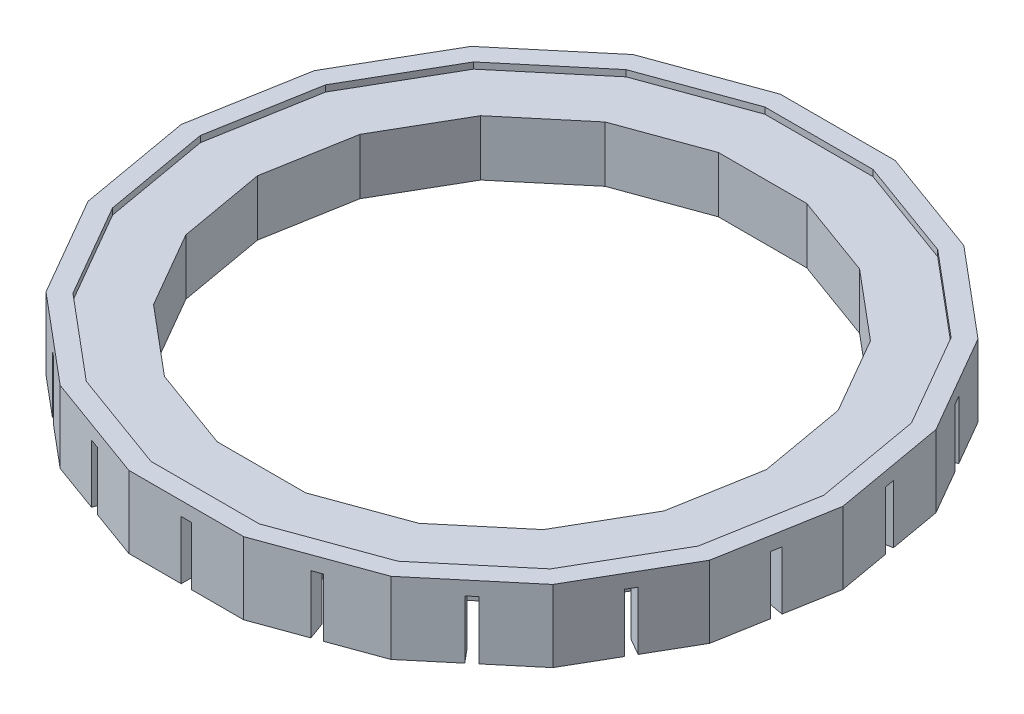
SolidWorks part; units mm, degrees
ref_plane "Front Plane" through (0, 0, 0) normal (0, 0, 1) x (1, 0, 0)
ref_plane "Top Plane" through (0, 0, 0) normal (0, 1, 0) x (1, 0, 0)
ref_plane "Right Plane" through (0, 0, 0) normal (1, 0, 0) x (0, 0, -1)
sketch "Sketch2" plane through (0, 0, 0) normal (0, 1, 0) x (1, 0, 0)
  line L1 (52.8022, 0) -> (49.6178, 18.0594)
  line L2 (49.6178, 18.0594) -> (40.4488, 33.9406)
  line L3 (40.4488, 33.9406) -> (26.4011, 45.728)
  line L4 (26.4011, 45.728) -> (9.169, 52)
  line L5 (9.169, 52) -> (-9.169, 52)
  line L6 (-9.169, 52) -> (-26.4011, 45.728)
  line L7 (-26.4011, 45.728) -> (-40.4488, 33.9406)
  line L8 (-40.4488, 33.9406) -> (-49.6178, 18.0594)
  line L9 (-49.6178, 18.0594) -> (-52.8022, 0)
  line L10 (-52.8022, 0) -> (-49.6178, -18.0594)
  line L11 (-49.6178, -18.0594) -> (-40.4488, -33.9406)
  line L12 (-40.4488, -33.9406) -> (-26.4011, -45.728)
  line L13 (-26.4011, -45.728) -> (-9.169, -52)
  line L14 (-9.169, -52) -> (9.169, -52)
  line L15 (9.169, -52) -> (26.4011, -45.728)
  line L16 (26.4011, -45.728) -> (40.4488, -33.9406)
  line L17 (40.4488, -33.9406) -> (49.6178, -18.0594)
  line L18 (49.6178, -18.0594) -> (52.8022, 0)
  circle A0 centre (0, 0) radius 52 construction
  dimension "D1" = 104
extrude "Boss-Extrude1" add sketch "Sketch2" along normal blind 11.5
sketch "Sketch3" plane through (0, 0, 0) normal (0, -1, 0) x (1, 0, 0)
  line L1 (40.6171, 0) -> (38.1676, 13.8919)
  line L2 (38.1676, 13.8919) -> (31.1145, 26.1081)
  line L3 (31.1145, 26.1081) -> (20.3085, 35.1754)
  line L4 (20.3085, 35.1754) -> (7.0531, 40)
  line L5 (7.0531, 40) -> (-7.0531, 40)
  line L6 (-7.0531, 40) -> (-20.3085, 35.1754)
  line L7 (-20.3085, 35.1754) -> (-31.1145, 26.1081)
  line L8 (-31.1145, 26.1081) -> (-38.1676, 13.8919)
  line L9 (-38.1676, 13.8919) -> (-40.6171, 0)
  line L10 (-40.6171, 0) -> (-38.1676, -13.8919)
  line L11 (-38.1676, -13.8919) -> (-31.1145, -26.1081)
  line L12 (-31.1145, -26.1081) -> (-20.3085, -35.1754)
  line L13 (-20.3085, -35.1754) -> (-7.0531, -40)
  line L14 (-7.0531, -40) -> (7.0531, -40)
  line L15 (7.0531, -40) -> (20.3085, -35.1754)
  line L16 (20.3085, -35.1754) -> (31.1145, -26.1081)
  line L17 (31.1145, -26.1081) -> (38.1676, -13.8919)
  line L18 (38.1676, -13.8919) -> (40.6171, 0)
  circle A0 centre (0, 0) radius 40 construction
  dimension "D1" = 80
extrude "Cut-Extrude1" cut sketch "Sketch3" against normal up to surface (11.5 mm away) up to face at (0, 11.5, 0)
sketch "Sketch4" plane through (0, 0, 0) normal (0, -1, 0) x (1, 0, 0)
  line L0 (-0.8, 52) -> (-0.8, 49)
  line L1 (-9.169, 52) -> (9.169, 52) construction
  line L2 (-0.8, 49) -> (-3.5, 49)
  line L3 (-3.5, 49) -> (-3.5, 41.9953)
  line L4 (-3.5, 41.9953) -> (3.5, 41.9953)
  line L5 (3.5, 41.9953) -> (3.5, 49)
  line L6 (3.5, 49) -> (0.8, 49)
  line L7 (0.8, 49) -> (0.8, 52)
  line L8 (0, 52) -> (0, 40) construction
  line L9 (7.0531, 40) -> (-7.0531, 40) construction
  line L10 (17.0333, 49.1376) -> (16.0072, 46.3186)
  line L11 (16.0072, 46.3186) -> (13.4701, 47.242)
  line L12 (13.4701, 47.242) -> (11.0743, 40.6598)
  line L13 (17.6522, 38.2656) -> (20.0479, 44.8479)
  line L14 (20.0479, 44.8479) -> (17.5107, 45.7713)
  line L15 (17.5107, 45.7713) -> (18.5368, 48.5904)
  line L16 (17.785, 48.864) -> (13.6808, 37.5877) construction
  line L17 (11.0743, 40.6598) -> (17.6522, 38.2656)
  line L18 (32.8121, 40.3485) -> (30.8838, 38.0504)
  line L19 (30.8838, 38.0504) -> (28.8154, 39.7859)
  line L20 (28.8154, 39.7859) -> (24.3129, 34.42)
  line L21 (29.6752, 29.9205) -> (34.1777, 35.2864)
  line L22 (34.1777, 35.2864) -> (32.1094, 37.0219)
  line L23 (32.1094, 37.0219) -> (34.0378, 39.3201)
  line L24 (33.425, 39.8343) -> (25.7115, 30.6418) construction
  line L25 (24.3129, 34.42) -> (29.6752, 29.9205)
  line L26 (44.6333, 26.6928) -> (42.0352, 25.1928)
  line L27 (42.0352, 25.1928) -> (40.6852, 27.5311)
  line L28 (40.6852, 27.5311) -> (34.619, 24.0287)
  line L29 (38.119, 17.9666) -> (44.1852, 21.4689)
  line L30 (44.1852, 21.4689) -> (42.8352, 23.8072)
  line L31 (42.8352, 23.8072) -> (45.4333, 25.3072)
  line L32 (45.0333, 26) -> (34.641, 20) construction
  line L33 (34.619, 24.0287) -> (38.119, 17.9666)
  line L34 (51.0711, 9.8176) -> (48.1167, 9.2966)
  line L35 (48.1167, 9.2966) -> (47.6478, 11.9556)
  line L36 (47.6478, 11.9556) -> (40.7495, 10.7392)
  line L37 (41.9651, 3.8456) -> (48.8633, 5.0619)
  line L38 (48.8633, 5.0619) -> (48.3945, 7.7209)
  line L39 (48.3945, 7.7209) -> (51.3489, 8.2419)
  line L40 (51.21, 9.0297) -> (39.3923, 6.9459) construction
  line L41 (40.7495, 10.7392) -> (41.9651, 3.8456)
  line L42 (51.3489, -8.2419) -> (48.3945, -7.7209)
  line L43 (48.3945, -7.7209) -> (48.8633, -5.0619)
  line L44 (48.8633, -5.0619) -> (41.9651, -3.8456)
  line L45 (40.7495, -10.7392) -> (47.6478, -11.9556)
  line L46 (47.6478, -11.9556) -> (48.1167, -9.2966)
  line L47 (48.1167, -9.2966) -> (51.0711, -9.8176)
  line L48 (51.21, -9.0297) -> (39.3923, -6.9459) construction
  line L49 (41.9651, -3.8456) -> (40.7495, -10.7392)
  line L50 (45.4333, -25.3072) -> (42.8352, -23.8072)
  line L51 (42.8352, -23.8072) -> (44.1852, -21.4689)
  line L52 (44.1852, -21.4689) -> (38.119, -17.9666)
  line L53 (34.619, -24.0287) -> (40.6852, -27.5311)
  line L54 (40.6852, -27.5311) -> (42.0352, -25.1928)
  line L55 (42.0352, -25.1928) -> (44.6333, -26.6928)
  line L56 (45.0333, -26) -> (34.641, -20) construction
  line L57 (38.119, -17.9666) -> (34.619, -24.0287)
  line L58 (34.0378, -39.3201) -> (32.1094, -37.0219)
  line L59 (32.1094, -37.0219) -> (34.1777, -35.2864)
  line L60 (34.1777, -35.2864) -> (29.6752, -29.9205)
  line L61 (24.3129, -34.42) -> (28.8154, -39.7859)
  line L62 (28.8154, -39.7859) -> (30.8838, -38.0504)
  line L63 (30.8838, -38.0504) -> (32.8121, -40.3485)
  line L64 (33.425, -39.8343) -> (25.7115, -30.6418) construction
  line L65 (29.6752, -29.9205) -> (24.3129, -34.42)
  line L66 (18.5368, -48.5904) -> (17.5107, -45.7713)
  line L67 (17.5107, -45.7713) -> (20.0479, -44.8479)
  line L68 (20.0479, -44.8479) -> (17.6522, -38.2656)
  line L69 (11.0743, -40.6598) -> (13.4701, -47.242)
  line L70 (13.4701, -47.242) -> (16.0072, -46.3186)
  line L71 (16.0072, -46.3186) -> (17.0333, -49.1376)
  line L72 (17.785, -48.864) -> (13.6808, -37.5877) construction
  line L73 (17.6522, -38.2656) -> (11.0743, -40.6598)
  line L74 (0.8, -52) -> (0.8, -49)
  line L75 (0.8, -49) -> (3.5, -49)
  line L76 (3.5, -49) -> (3.5, -41.9953)
  line L77 (-3.5, -41.9953) -> (-3.5, -49)
  line L78 (-3.5, -49) -> (-0.8, -49)
  line L79 (-0.8, -49) -> (-0.8, -52)
  line L80 (0, -52) -> (0, -40) construction
  line L81 (3.5, -41.9953) -> (-3.5, -41.9953)
  line L82 (-17.0333, -49.1376) -> (-16.0072, -46.3186)
  line L83 (-16.0072, -46.3186) -> (-13.4701, -47.242)
  line L84 (-13.4701, -47.242) -> (-11.0743, -40.6598)
  line L85 (-17.6522, -38.2656) -> (-20.0479, -44.8479)
  line L86 (-20.0479, -44.8479) -> (-17.5107, -45.7713)
  line L87 (-17.5107, -45.7713) -> (-18.5368, -48.5904)
  line L88 (-17.785, -48.864) -> (-13.6808, -37.5877) construction
  line L89 (-11.0743, -40.6598) -> (-17.6522, -38.2656)
  line L90 (-32.8121, -40.3485) -> (-30.8838, -38.0504)
  line L91 (-30.8838, -38.0504) -> (-28.8154, -39.7859)
  line L92 (-28.8154, -39.7859) -> (-24.3129, -34.42)
  line L93 (-29.6752, -29.9205) -> (-34.1777, -35.2864)
  line L94 (-34.1777, -35.2864) -> (-32.1094, -37.0219)
  line L95 (-32.1094, -37.0219) -> (-34.0378, -39.3201)
  line L96 (-33.425, -39.8343) -> (-25.7115, -30.6418) construction
  line L97 (-24.3129, -34.42) -> (-29.6752, -29.9205)
  line L98 (-44.6333, -26.6928) -> (-42.0352, -25.1928)
  line L99 (-42.0352, -25.1928) -> (-40.6852, -27.5311)
  line L100 (-40.6852, -27.5311) -> (-34.619, -24.0287)
  line L101 (-38.119, -17.9666) -> (-44.1852, -21.4689)
  line L102 (-44.1852, -21.4689) -> (-42.8352, -23.8072)
  line L103 (-42.8352, -23.8072) -> (-45.4333, -25.3072)
  line L104 (-45.0333, -26) -> (-34.641, -20) construction
  line L105 (-34.619, -24.0287) -> (-38.119, -17.9666)
  line L106 (-51.0711, -9.8176) -> (-48.1167, -9.2966)
  line L107 (-48.1167, -9.2966) -> (-47.6478, -11.9556)
  line L108 (-47.6478, -11.9556) -> (-40.7495, -10.7392)
  line L109 (-41.9651, -3.8456) -> (-48.8633, -5.0619)
  line L110 (-48.8633, -5.0619) -> (-48.3945, -7.7209)
  line L111 (-48.3945, -7.7209) -> (-51.3489, -8.2419)
  line L112 (-51.21, -9.0297) -> (-39.3923, -6.9459) construction
  line L113 (-40.7495, -10.7392) -> (-41.9651, -3.8456)
  line L114 (-51.3489, 8.2419) -> (-48.3945, 7.7209)
  line L115 (-48.3945, 7.7209) -> (-48.8633, 5.0619)
  line L116 (-48.8633, 5.0619) -> (-41.9651, 3.8456)
  line L117 (-40.7495, 10.7392) -> (-47.6478, 11.9556)
  line L118 (-47.6478, 11.9556) -> (-48.1167, 9.2966)
  line L119 (-48.1167, 9.2966) -> (-51.0711, 9.8176)
  line L120 (-51.21, 9.0297) -> (-39.3923, 6.9459) construction
  line L121 (-41.9651, 3.8456) -> (-40.7495, 10.7392)
  line L122 (-45.4333, 25.3072) -> (-42.8352, 23.8072)
  line L123 (-42.8352, 23.8072) -> (-44.1852, 21.4689)
  line L124 (-44.1852, 21.4689) -> (-38.119, 17.9666)
  line L125 (-34.619, 24.0287) -> (-40.6852, 27.5311)
  line L126 (-40.6852, 27.5311) -> (-42.0352, 25.1928)
  line L127 (-42.0352, 25.1928) -> (-44.6333, 26.6928)
  line L128 (-45.0333, 26) -> (-34.641, 20) construction
  line L129 (-38.119, 17.9666) -> (-34.619, 24.0287)
  line L130 (-34.0378, 39.3201) -> (-32.1094, 37.0219)
  line L131 (-32.1094, 37.0219) -> (-34.1777, 35.2864)
  line L132 (-34.1777, 35.2864) -> (-29.6752, 29.9205)
  line L133 (-24.3129, 34.42) -> (-28.8154, 39.7859)
  line L134 (-28.8154, 39.7859) -> (-30.8838, 38.0504)
  line L135 (-30.8838, 38.0504) -> (-32.8121, 40.3485)
  line L136 (-33.425, 39.8343) -> (-25.7115, 30.6418) construction
  line L137 (-29.6752, 29.9205) -> (-24.3129, 34.42)
  line L138 (-18.5368, 48.5904) -> (-17.5107, 45.7713)
  line L139 (-17.5107, 45.7713) -> (-20.0479, 44.8479)
  line L140 (-20.0479, 44.8479) -> (-17.6522, 38.2656)
  line L141 (-11.0743, 40.6598) -> (-13.4701, 47.242)
  line L142 (-13.4701, 47.242) -> (-16.0072, 46.3186)
  line L143 (-16.0072, 46.3186) -> (-17.0333, 49.1376)
  line L144 (-17.785, 48.864) -> (-13.6808, 37.5877) construction
  line L145 (-17.6522, 38.2656) -> (-11.0743, 40.6598)
  line L147 (-0.8, 52) -> (0.8, 52)
  line L148 (17.0333, 49.1376) -> (18.5368, 48.5904)
  line L149 (32.8121, 40.3485) -> (34.0378, 39.3201)
  line L150 (44.6333, 26.6928) -> (45.4333, 25.3072)
  line L151 (51.0711, 9.8176) -> (51.3489, 8.2419)
  line L152 (51.3489, -8.2419) -> (51.0711, -9.8176)
  line L153 (45.4333, -25.3072) -> (44.6333, -26.6928)
  line L154 (34.0378, -39.3201) -> (32.8121, -40.3485)
  line L155 (18.5368, -48.5904) -> (17.0333, -49.1376)
  line L156 (-0.8, -52) -> (0.8, -52)
  line L157 (-18.5368, -48.5904) -> (-17.0333, -49.1376)
  line L159 (-34.0378, -39.3201) -> (-32.8121, -40.3485)
  line L160 (-45.4333, -25.3072) -> (-44.6333, -26.6928)
  line L161 (-51.3489, -8.2419) -> (-51.0711, -9.8176)
  line L162 (-51.0711, 9.8176) -> (-51.3489, 8.2419)
  line L163 (-44.6333, 26.6928) -> (-45.4333, 25.3072)
  line L164 (-32.8121, 40.3485) -> (-34.0378, 39.3201)
  line L165 (-17.0333, 49.1376) -> (-18.5368, 48.5904)
  point P191 (0, 0)
  dimension "D1" = 0.0682
  dimension "D2" = 0.1325
  dimension "D3" = 1.348
  dimension "D4" = 1.4182
  dimension "D5" = 4.0163
  dimension "D7" = 18
extrude "Cut-Extrude3" cut sketch "Sketch4" against normal blind 9.3
sketch "Sketch5" plane through (0, 0, 0) normal (0, -1, 0) x (1, 0, 0)
  line L1 (49.75, 0) -> (46.7497, 17.0155)
  line L2 (46.7497, 17.0155) -> (38.1107, 31.9787)
  line L3 (38.1107, 31.9787) -> (24.875, 43.0848)
  line L4 (24.875, 43.0848) -> (8.639, 48.9942)
  line L5 (8.639, 48.9942) -> (-8.639, 48.9942)
  line L6 (-8.639, 48.9942) -> (-24.875, 43.0848)
  line L7 (-24.875, 43.0848) -> (-38.1107, 31.9787)
  line L8 (-38.1107, 31.9787) -> (-46.7497, 17.0155)
  line L9 (-46.7497, 17.0155) -> (-49.75, 0)
  line L10 (-49.75, 0) -> (-46.7497, -17.0155)
  line L11 (-46.7497, -17.0155) -> (-38.1107, -31.9787)
  line L12 (-38.1107, -31.9787) -> (-24.875, -43.0848)
  line L13 (-24.875, -43.0848) -> (-8.639, -48.9942)
  line L14 (-8.639, -48.9942) -> (8.639, -48.9942)
  line L15 (8.639, -48.9942) -> (24.875, -43.0848)
  line L16 (24.875, -43.0848) -> (38.1107, -31.9787)
  line L17 (38.1107, -31.9787) -> (46.7497, -17.0155)
  line L18 (46.7497, -17.0155) -> (49.75, 0)
  circle A0 centre (0, 0) radius 48.9942 construction
  dimension "D1" = 99.5
extrude "Cut-Extrude4" cut sketch "Sketch5" against normal blind 1.6
sketch "Sketch6" plane through (0, 11.5, 0) normal (0, 1, 0) x (1, 0, 0)
  line L1 (49.75, 0) -> (46.7497, 17.0155)
  line L2 (46.7497, 17.0155) -> (38.1107, 31.9787)
  line L3 (38.1107, 31.9787) -> (24.875, 43.0848)
  line L4 (24.875, 43.0848) -> (8.639, 48.9942)
  line L5 (8.639, 48.9942) -> (-8.639, 48.9942)
  line L6 (-8.639, 48.9942) -> (-24.875, 43.0848)
  line L7 (-24.875, 43.0848) -> (-38.1107, 31.9787)
  line L8 (-38.1107, 31.9787) -> (-46.7497, 17.0155)
  line L9 (-46.7497, 17.0155) -> (-49.75, 0)
  line L10 (-49.75, 0) -> (-46.7497, -17.0155)
  line L11 (-46.7497, -17.0155) -> (-38.1107, -31.9787)
  line L12 (-38.1107, -31.9787) -> (-24.875, -43.0848)
  line L13 (-24.875, -43.0848) -> (-8.639, -48.9942)
  line L14 (-8.639, -48.9942) -> (8.639, -48.9942)
  line L15 (8.639, -48.9942) -> (24.875, -43.0848)
  line L16 (24.875, -43.0848) -> (38.1107, -31.9787)
  line L17 (38.1107, -31.9787) -> (46.7497, -17.0155)
  line L18 (46.7497, -17.0155) -> (49.75, 0)
  circle A0 centre (0, 0) radius 48.9942 construction
  dimension "D1" = 99.5
extrude "Cut-Extrude5" cut sketch "Sketch6" against normal blind 1
